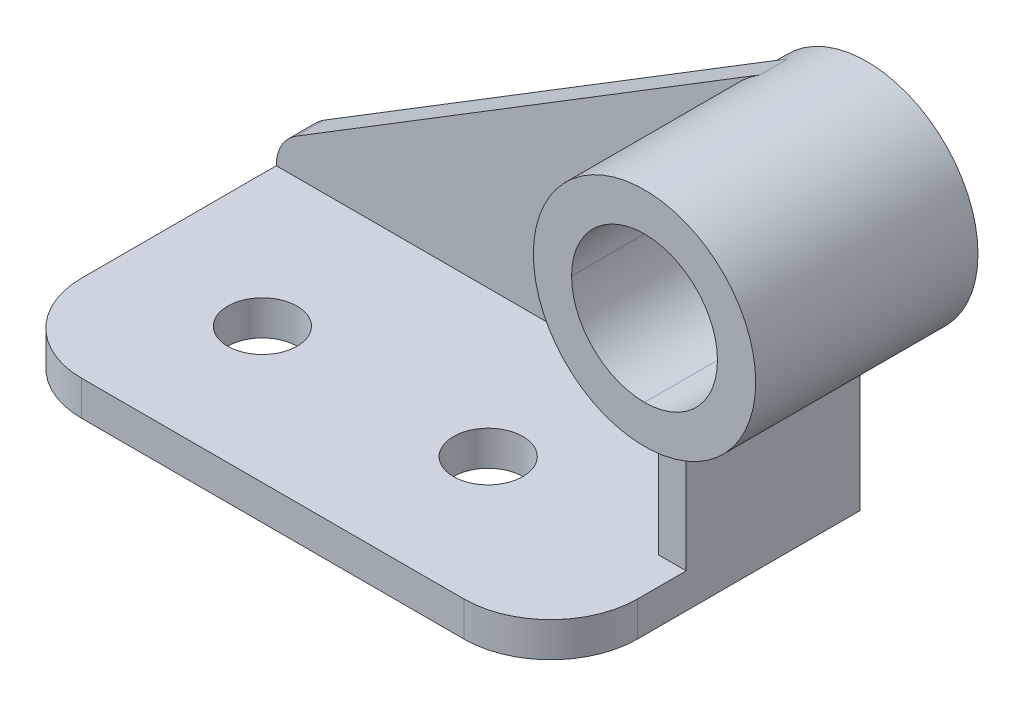
SolidWorks part; units mm, degrees
material "Alloy Steel"
ref_plane "Front" through (0, 0, 0) normal (0, 0, 1) x (1, 0, 0)
ref_plane "Top" through (0, 0, 0) normal (0, 1, 0) x (1, 0, 0)
ref_plane "Right" through (0, 0, 0) normal (1, 0, 0) x (0, 0, -1)
other "Configuration Table"
sketch "Sketch1" plane through (0, 0, 0) normal (0, 1, 0) x (1, 0, 0)
  line L0 (25, 0) -> (135, 0)
  line L1 (0, 25) -> (0, 89)
  line L2 (160, 89) -> (0, 89)
  line L3 (160, 89) -> (160, 25)
  arc A0 (25, 0) -> (0, 25) centre (25, 25) cw
  arc A1 (160, 25) -> (135, 0) centre (135, 25) cw
  dimension "D1" = 25
  dimension "D2" = 25
  dimension "D3" = 89
  dimension "D4" = 160
extrude "Base-Extrude" add sketch "Sketch1" along normal blind 10
sketch "Sketch2" plane through (0, 0, -89) normal (0, 0, -1) x (-1, 0, 0)
  line L0 (-160, 0) -> (0, 0) construction
  line L1 (0, 10) -> (0, 0) construction
  line L2 (-160, 10) -> (0, 10) construction
  line L3 (-160, 10) -> (0, 10)
  line L4 (-160, 10) -> (-160, 0) construction
  line L5 (-160, 10) -> (-160, 43.251)
  line L6 (-5.7182, 20.2244) -> (-139.2484, 102.2651)
  arc A0 (-139.2484, 102.2651) -> (-160, 43.251) centre (-156, 75) ccw
  arc A1 (0, 10) -> (-5.7182, 20.2244) centre (-12, 10) ccw
  dimension "D1" = 64
  dimension "D4" = 12
  dimension "D2" = 75
  dimension "D3" = 156
extrude "Boss-Extrude1" add sketch "Sketch2" against normal blind 8
ref_plane "Plane4" through (0, 0, -95) normal (0, 0, -1) x (-1, 0, 0)
sketch "Sketch3" plane through (0, 0, -95) normal (0, 0, -1) x (-1, 0, 0)
  circle A0 centre (-156, 75) radius 32
  arc A1 (-139.2484, 102.2651) -> (-160, 43.251) centre (-156, 75) ccw construction
extrude "Boss-Extrude2" add sketch "Sketch3" against normal blind 64
sketch "Sketch7" plane through (0, 0, -95) normal (0, 0, -1) x (-1, 0, 0)
  circle A0 centre (-156, 75) radius 21
  dimension "D1" = 42
extrude "Cut-Extrude1" cut sketch "Sketch7" against normal through all
sketch "Sketch4" plane through (0, 10, 0) normal (0, 1, 0) x (-1, 0, 0)
  line L1 (-152, -81) -> (-152, -25)
  line L2 (-152, -81) -> (-152, -39)
  line L3 (-160, -39) -> (0, -39)
  line L4 (-160, -81) -> (-160, -25) construction
  line L5 (-160, -81) -> (-160, -39)
  line L6 (-160, -81) -> (0, -81) construction
  line L7 (-160, -81) -> (-152, -81)
  line L8 (-160, -39) -> (-152, -39)
  dimension "D1" = 8
  dimension "D2" = 50
extrude "Boss-Extrude3" add sketch "Sketch4" along normal up to next
hole_wizard "Hole1" positions "Sketch5" profile "Sketch6" legacy end condition through all
sketch "Sketch5" plane through (0, 10, 0) normal (0, 1, 0) x (-1, 0, 0)
  line L0 (0, -25) -> (0, -81) construction
  line L2 (-5.7182, -89) -> (-139.2484, -89) construction
  point P0 (-38, -39)
  dimension "D1" = 38
  dimension "D2" = 50
sketch "Sketch6" plane through (38, 10, -39) normal (1, 0, 0) x (0, 0, 1)
  line L0 (0, 0) -> (0, 10)
  line L1 (0, 10) -> (10, 10)
  line L2 (10, 10) -> (10, 0)
  line L3 (10, 0) -> (0, 0)
pattern_linear "LPattern1" count 2 spacing 65 along (1, 0, 0) of "Hole1"
ref_plane "Plane5" through (0, 75, 0) normal (0, 1, 0) x (-1, 0, 0)
sketch "Sketch9" plane through (0, 75, 0) normal (0, 1, 0) x (-1, 0, 0)
  line L0 (-156, -31) -> (-156, -95)
  line L1 (-135, -31) -> (-177, -31) construction
  line L2 (-124, -95) -> (-188, -95) construction
split line "Split Line1"
ref_plane "Plane7" through (156, 0, 0) normal (1, 0, 0) x (0, 0, -1)
sketch "Sketch14" plane through (156, 0, 0) normal (1, 0, 0) x (0, 0, -1)
  line L2 (31, 75) -> (95, 75)
  line L3 (31, 107) -> (31, 43) construction
  line L4 (95, 107) -> (95, 43) construction
split line "Split Line2"
